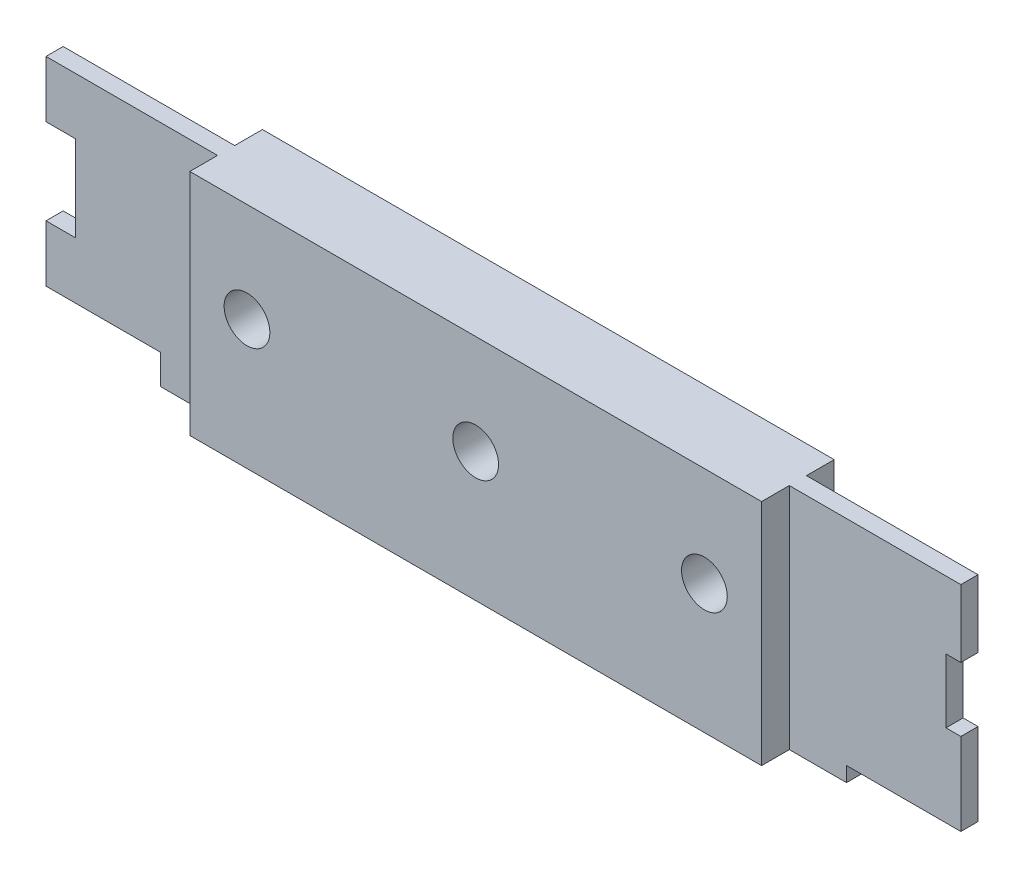
SolidWorks part; units mm, degrees
ref_plane "Alzado" through (0, 0, 0) normal (0, 0, 1) x (1, 0, 0)
ref_plane "Planta" through (0, 0, 0) normal (0, 1, 0) x (1, 0, 0)
ref_plane "Vista lateral" through (0, 0, 0) normal (1, 0, 0) x (0, 0, -1)
sketch "Croquis1" plane through (0, 0, 0) normal (0, 0, 1) x (1, 0, 0)
  line L0 (-40, 8.7) -> (40, 8.7)
  line L1 (40, 8.7) -> (40, 2.8)
  line L2 (40, 2.8) -> (38.7, 2.8)
  line L3 (38.7, 2.8) -> (38.7, -2.8)
  line L4 (38.7, -2.8) -> (40, -2.8)
  line L5 (40, -2.8) -> (40, -10)
  line L6 (40, -10) -> (30, -10)
  line L7 (30, -10) -> (30, -11.3)
  line L8 (30, -11.3) -> (-30, -11.3)
  line L9 (-30, -11.3) -> (-30, -8.7)
  line L10 (-30, -8.7) -> (-40, -8.7)
  line L11 (-40, -8.7) -> (-40, -3.75)
  line L12 (-40, -3.75) -> (-37.4, -3.75)
  line L13 (-37.4, -3.75) -> (-37.4, 3.75)
  line L14 (-37.4, 3.75) -> (-40, 3.75)
  line L15 (-40, 3.75) -> (-40, 8.7)
  line L16 (38.7, 0) -> (-37.4, 0) construction
  circle A0 centre (20, 0) radius 2
  circle A1 centre (0, 0) radius 2
  circle A2 centre (-20, 0) radius 2
  point P16 (-37.4, 0)
  point P18 (38.7, 0)
  point P19 (0, 8.7)
  dimension "D9" = 4
  dimension "D10" = 20
  dimension "D11" = 20
  dimension "D12" = 20
  dimension "D1" = 80
  dimension "D2" = 10
  dimension "D3" = 10
  dimension "D4" = 20
  dimension "D5" = 7.5
  dimension "D6" = 5.6
  dimension "D7" = 2.6
  dimension "D8" = 1.3
extrude "Saliente-Extruir1" add sketch "Croquis1" along normal mid plane 1.5
sketch "Croquis2" plane through (0, 0, 0) normal (0, 0, 1) x (1, 0, 0)
  line L0 (40, 8.7) -> (-40, 8.7) construction
  line L1 (-25, 8.7) -> (25, 8.7)
  line L2 (-25, 8.7) -> (-25, -11.3)
  line L3 (-25, -11.3) -> (25, -11.3)
  line L4 (25, 8.7) -> (25, -11.3)
  line L5 (-30, -11.3) -> (30, -11.3) construction
  line L6 (-40, 8.7) -> (-40, 3.75) construction
  line L7 (40, 2.8) -> (40, 8.7) construction
  circle A0 centre (-20, 0) radius 2
  circle A1 centre (0, 0) radius 2
  circle A2 centre (20, 0) radius 2
  dimension "D1" = 15
  dimension "D2" = 15
extrude "Saliente-Extruir2" add sketch "Croquis2" along normal mid plane 6.35
